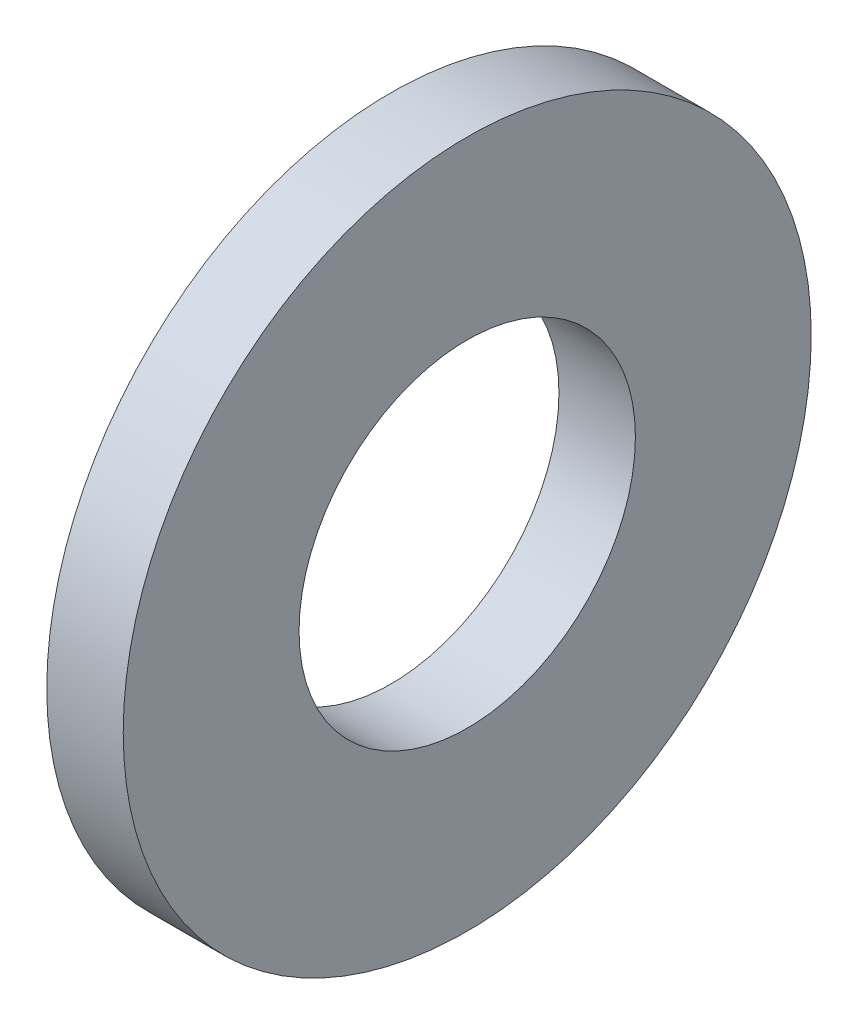
SolidWorks part; units mm, degrees
ref_plane "Plane1" through (0, 0, 0) normal (0, 0, 1) x (1, 0, 0)
ref_plane "Plane2" through (0, 0, 0) normal (0, 1, 0) x (1, 0, 0)
ref_plane "Plane3" through (0, 0, 0) normal (1, 0, 0) x (0, 0, -1)
sketch "Sketch1" plane through (0, 0, 0) normal (1, 0, 0) x (0, 0, -1)
  circle A0 centre (0, 0) radius 4.4
  circle A1 centre (0, 0) radius 9
  dimension "Insid_dia" = 8.8
  dimension "OutsideDia" = 18
extrude "Base-Extrude" add sketch "Sketch1" along normal blind 2
